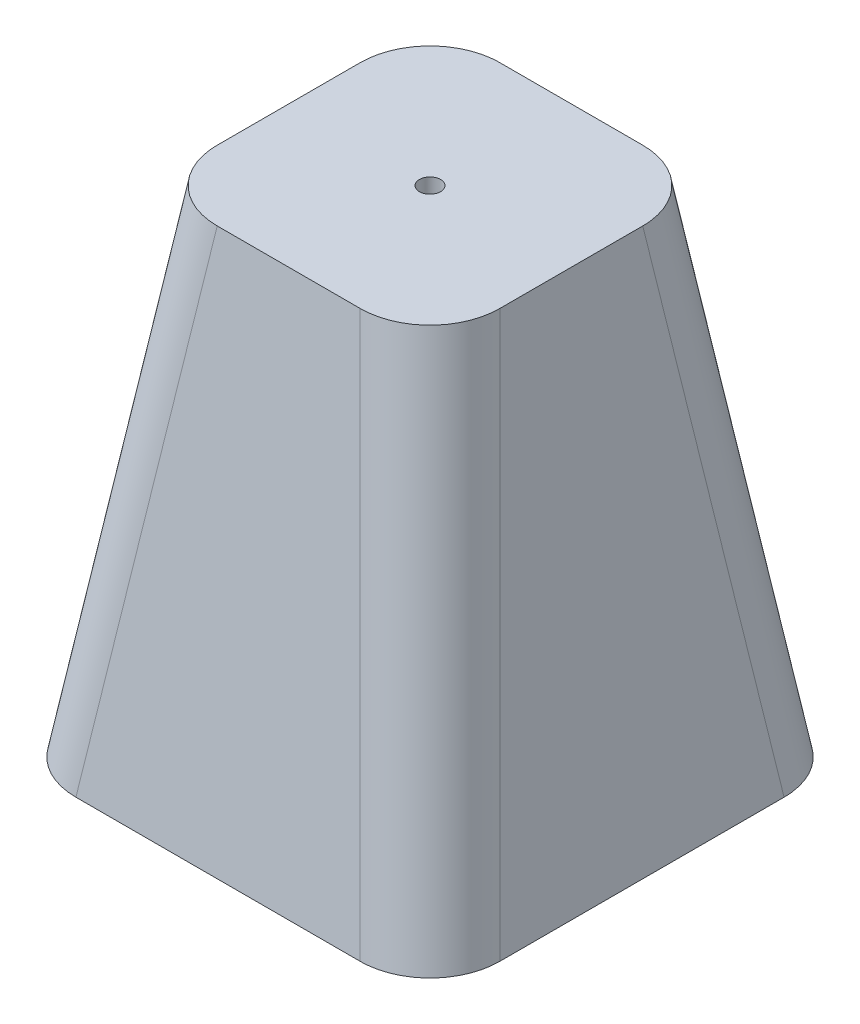
SolidWorks part; units mm, degrees
ref_plane "Front Plane" through (0, 0, 0) normal (0, 0, 1) x (1, 0, 0)
ref_plane "Top Plane" through (0, 0, 0) normal (0, 1, 0) x (1, 0, 0)
ref_plane "Right Plane" through (0, 0, 0) normal (1, 0, 0) x (0, 0, -1)
sketch "Sketch1" plane through (0, 0, 0) normal (0, 1, 0) x (1, 0, 0)
  line L1 (-30, -30) -> (30, -30)
  line L2 (-30, -30) -> (-30, 30)
  line L3 (-30, 30) -> (30, 30)
  line L4 (30, -30) -> (30, 30)
  line L5 (-30, -30) -> (30, 30) construction
  line L6 (-30, 30) -> (30, -30) construction
  point P0 (0, 0)
  dimension "D1" = 60
ref_plane "Plane1" through (0, 70, 0) normal (0, 1, 0) x (1, 0, 0)
sketch "Sketch2" plane through (0, 70, 0) normal (0, 1, 0) x (1, 0, 0)
  line L1 (-20, -20) -> (20, -20)
  line L2 (-20, -20) -> (-20, 20)
  line L3 (-20, 20) -> (20, 20)
  line L4 (20, -20) -> (20, 20)
  line L5 (-20, -20) -> (20, 20) construction
  line L6 (-20, 20) -> (20, -20) construction
  point P0 (0, 0)
  dimension "D1" = 40
loft "Loft1" add profiles "Sketch2", "Sketch1"
sketch "Sketch3" plane through (0, 0, 0) normal (0, -1, 0) x (1, 0, 0)
  circle A0 centre (0, 0) radius 1.5
  dimension "D1" = 3
extrude "Cut-Extrude1" cut sketch "Sketch3" against normal blind 3
ref_plane "Plane2" through (0, 35, 0) normal (0, -1, 0) x (-1, 0, 0)
mirror "Mirror1" about plane through (0, 35, 0) normal (0, -1, 0) of "Cut-Extrude1"
fillet "Fillet1" radius 10 4 edges
